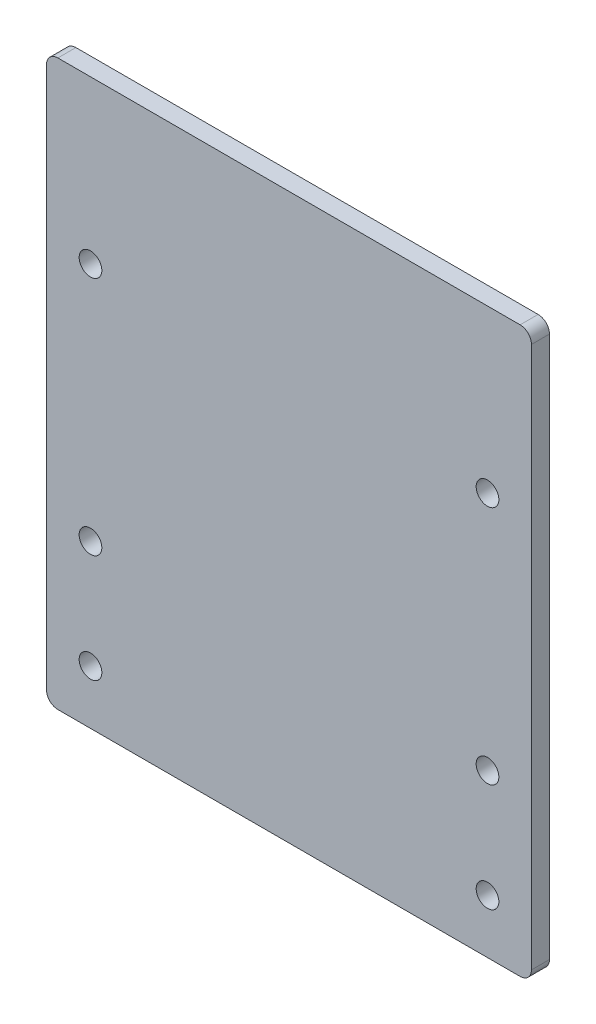
SolidWorks part; units mm, degrees
ref_plane "Front Plane" through (0, 0, 0) normal (0, 0, 1) x (1, 0, 0)
ref_plane "Top Plane" through (0, 0, 0) normal (0, 1, 0) x (1, 0, 0)
ref_plane "Right Plane" through (0, 0, 0) normal (1, 0, 0) x (0, 0, -1)
sketch "Sketch1" plane through (0, 0, 0) normal (0, 0, 1) x (1, 0, 0)
  line L0 (-42.75, -12.7) -> (42.75, -12.7) construction
  line L5 (-40.75, 0) -> (40.75, 0)
  line L6 (-42.75, -2) -> (-42.75, -97.5)
  line L7 (-40.75, -99.5) -> (40.75, -99.5)
  line L8 (42.75, -2) -> (42.75, -97.5)
  line L9 (-42.75, -86.8) -> (42.75, -86.8) construction
  arc A4 (40.75, -99.5) -> (42.75, -97.5) centre (40.75, -97.5) ccw
  arc A5 (-42.75, -97.5) -> (-40.75, -99.5) centre (-40.75, -97.5) ccw
  arc A6 (40.75, 0) -> (42.75, -2) centre (40.75, -2) cw
  arc A7 (-40.75, 0) -> (-42.75, -2) centre (-40.75, -2) ccw
  circle A10 centre (35, -89.975) radius 2
  circle A11 centre (-35, -89.975) radius 2
  circle A12 centre (35, -70.925) radius 2
  circle A13 centre (35, -28.58) radius 2
  circle A14 centre (-35, -70.92) radius 2
  circle A15 centre (-35, -28.58) radius 2
  point P8 (-42.75, -99.5)
  point P11 (42.75, 0)
  point P14 (-42.75, 0)
  point P36 (0, 0)
  dimension "D3" = 2
  dimension "D4" = 12.7
  dimension "D12" = 4
  dimension "D13" = 4
  dimension "D14" = 70
  dimension "D16" = 4
  dimension "D17" = 4
  dimension "D20" = 4
  dimension "D21" = 4
  dimension "D1" = 85.5
  dimension "D2" = 99.5
  dimension "D10" = 12.7
  dimension "D11" = 9.525
  dimension "D15" = 7.75
  dimension "D18" = 19.05
  dimension "D19" = 28.58
  dimension "D22" = 28.58
  dimension "D23" = 28.58
extrude "Boss-Extrude1" add sketch "Sketch1" along normal blind 3.175
